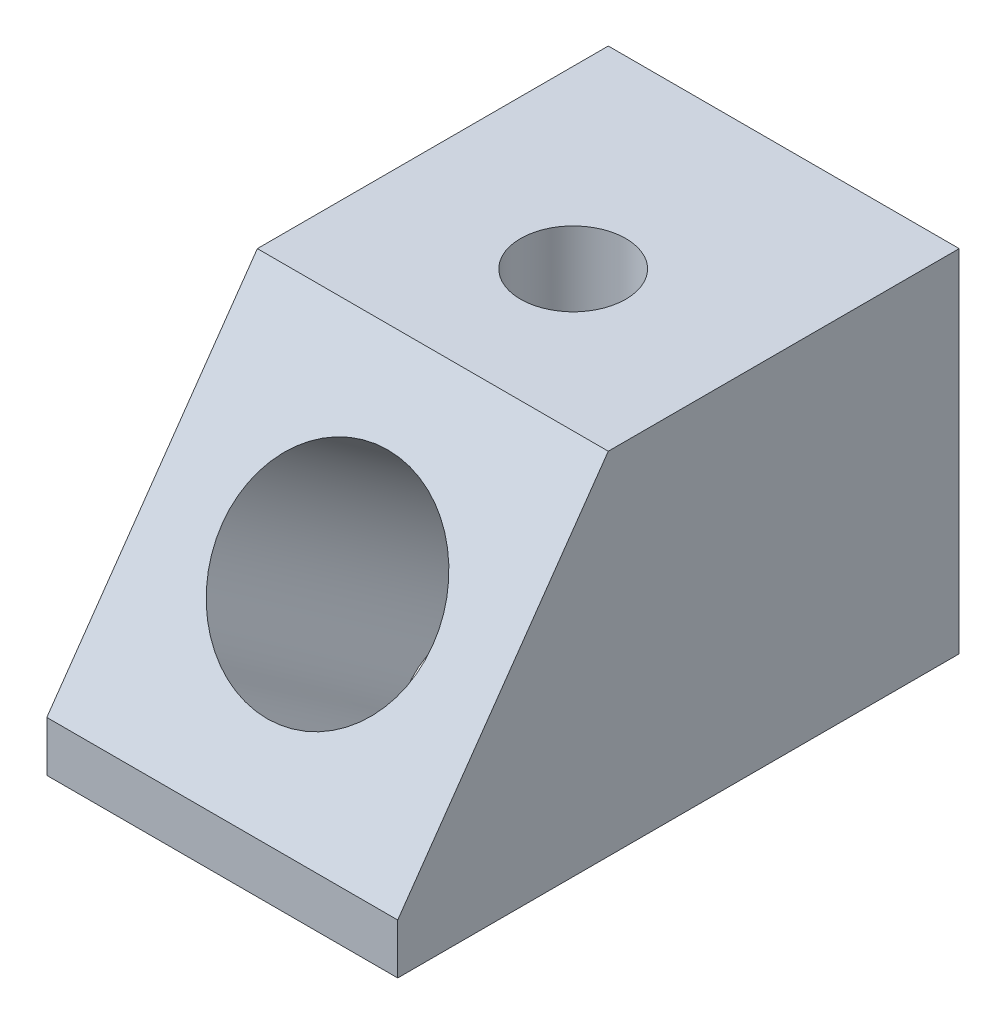
SolidWorks part; units mm, degrees
ref_plane "前视基准面" through (0, 0, 0) normal (0, 0, 1) x (1, 0, 0)
ref_plane "上视基准面" through (0, 0, 0) normal (0, 1, 0) x (1, 0, 0)
ref_plane "右视基准面" through (0, 0, 0) normal (1, 0, 0) x (0, 0, -1)
other "Configuration Table"
sketch "草图1" plane through (0, 0, 0) normal (0, 1, 0) x (1, 0, 0)
  line L1 (0, 0) -> (10, 0)
  line L2 (0, 0) -> (0, 16)
  line L3 (0, 16) -> (10, 16)
  line L4 (10, 0) -> (10, 16)
  circle A0 centre (5, 10) radius 1.5
  dimension "D3" = 3
  dimension "D1" = 10
  dimension "D2" = 16
  dimension "D4" = 10
  dimension "D5" = 5
extrude "凸台-拉伸1" add sketch "草图1" along normal blind 10
sketch "草图2" plane through (10, 0, 0) normal (1, 0, 0) x (0, 0, -1)
  line L0 (0, 1.4311) -> (6, 10)
  line L1 (0, 10) -> (0, 0) construction
  line L2 (0, 10) -> (16, 10) construction
  line L3 (0, 1.4311) -> (0, 10)
  line L4 (0, 10) -> (6, 10)
  dimension "D1" = 55
  dimension "D2" = 6
extrude "切除-拉伸1" cut sketch "草图2" against normal up to surface (10 mm away) up to face at (0, 5, -8)
sketch "草图3" plane through (0, 0.4708, 0.6724) normal (0, 0.5736, 0.8192) x (1, 0, 0)
  line L0 (0, 11.633) -> (10, 1.1723) construction
  line L1 (0, 1.1723) -> (10, 11.633) construction
  line L2 (10, 1.1723) -> (10, 11.633) construction
  circle A0 centre (5, 6.4026) radius 3
  dimension "D1" = 6
extrude "切除-拉伸2" cut sketch "草图3" against normal through all contours A0
